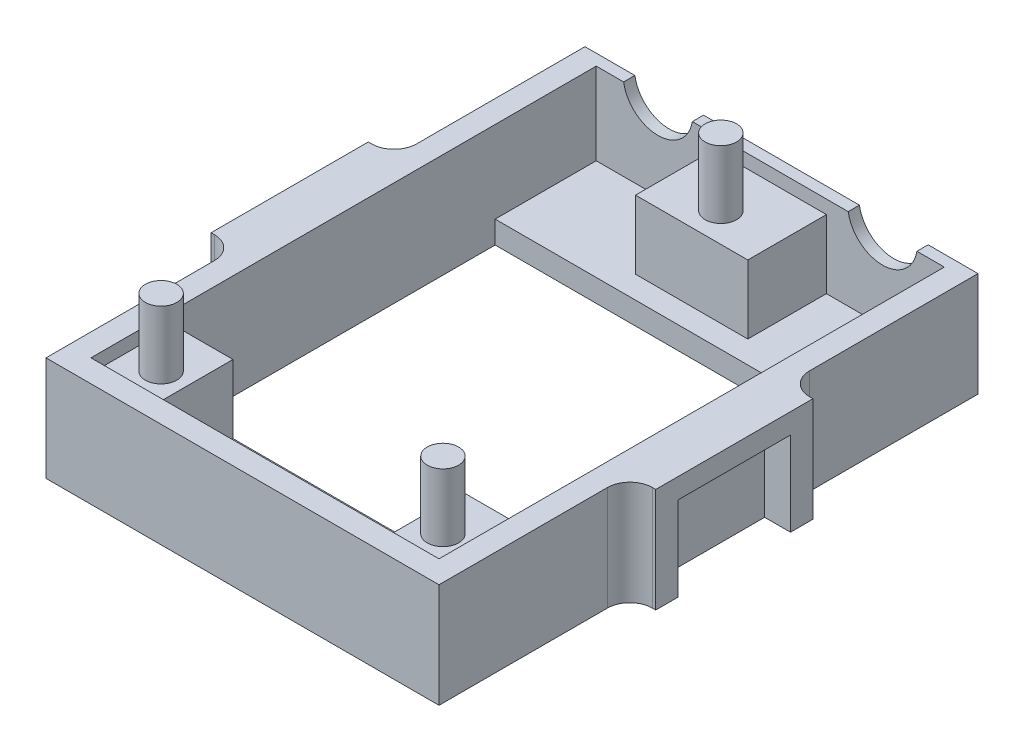
SolidWorks part; units mm, degrees
ref_plane "Front Plane" through (0, 0, 0) normal (0, 0, 1) x (1, 0, 0)
ref_plane "Top Plane" through (0, 0, 0) normal (0, 1, 0) x (1, 0, 0)
ref_plane "Right Plane" through (0, 0, 0) normal (1, 0, 0) x (0, 0, -1)
sketch "Sketch1" plane through (0, 0, 0) normal (0, 1, 0) x (1, 0, 0)
  line L1 (-17.5, 24) -> (17.5, 24)
  line L2 (-17.5, 24) -> (-17.5, -24)
  line L3 (-17.5, -24) -> (17.5, -24)
  line L4 (17.5, 24) -> (17.5, -24)
  line L5 (-44.2539, 0) -> (44.2539, 0) construction
  line L6 (0, -44.7868) -> (0, 44.7868) construction
  dimension "D2" = 35
  dimension "D1" = 48
  dimension "D3" = 24
  dimension "D4" = 17.5
extrude "Boss-Extrude1" add sketch "Sketch1" along normal blind 2
sketch "Sketch2" plane through (0, 2, 0) normal (0, 1, 0) x (1, 0, 0)
  line L1 (-15.5, 23) -> (15.5, 23)
  line L2 (-15.5, 23) -> (-15.5, -21)
  line L3 (-15.5, -21) -> (15.5, -21)
  line L4 (15.5, 23) -> (15.5, -21)
  line L6 (17.5, -24) -> (17.5, 24) construction
  line L7 (-17.5, -24) -> (17.5, -24) construction
  line M5 (-17.5, 24) -> (-17.5, -24)
  line M6 (-17.5, -24) -> (17.5, -24)
  line M7 (17.5, -24) -> (17.5, 24)
  line M8 (17.5, 24) -> (-17.5, 24)
  dimension "D1" = 2
  dimension "D2" = 3
  dimension "D3" = 31
  dimension "D4" = 44
extrude "Boss-Extrude2" add sketch "Sketch2" along normal blind 7.3 contours L1 L4 L3 L2 M8 M5 M6 M7
sketch "Sketch3" plane through (0, 2, 0) normal (0, 1, 0) x (1, 0, 0)
  line L0 (-15.5, 23) -> (15.5, 23) construction
  line L1 (-5, 23) -> (5, 23)
  line L2 (-5, 23) -> (-5, 16)
  line L3 (-5, 16) -> (5, 16)
  line L4 (5, 23) -> (5, 16)
  line L5 (15.5, 23) -> (15.5, -21) construction
  line L7 (-15.5, -21) -> (-10.25, -21)
  line L8 (-15.5, -21) -> (-15.5, -14.6)
  line L9 (-15.5, -14.6) -> (-10.25, -14.6)
  line L10 (-10.25, -21) -> (-10.25, -14.6)
  line L11 (15.5, -21) -> (10.25, -21)
  line L12 (15.5, -21) -> (15.5, -14.6)
  line L13 (15.5, -14.6) -> (10.25, -14.6)
  line L14 (10.25, -21) -> (10.25, -14.6)
  dimension "D1" = 10
  dimension "D2" = 7
  dimension "D3" = 10.5
  dimension "D4" = 5.25
  dimension "D5" = 5.25
  dimension "D6" = 6.4
  dimension "D7" = 6.4
extrude "Boss-Extrude3" add sketch "Sketch3" along normal blind 6.1
sketch "Sketch6" plane through (0, 0, -24) normal (0, 0, -1) x (-1, 0, 0)
  line L1 (-17.5, 9.3) -> (17.5, 9.3) construction
  line L2 (-17.5, 9.3) -> (-17.5, 0) construction
  arc A0 (-6.9406, 9.3) -> (-13.0594, 9.3) centre (-10, 9.8) cw
  arc A1 (13.0594, 9.3) -> (6.9406, 9.3) centre (10, 9.8) cw
  line M3 (17.5, 9.3) -> (-17.5, 9.3)
  dimension "D1" = 7.5
  dimension "D3" = 0.5
  dimension "D4" = 0.5
  dimension "D5" = 3.1
  dimension "D6" = 3.1
  dimension "D2" = 20
sketch "Sketch8" plane through (0, 0, 0) normal (0, 1, 0) x (1, 0, 0)
  line L0 (0, -44.7868) -> (0, 44.7868) construction
  line L2 (17.5, 24) -> (-17.5, 24) construction
  circle A0 centre (-12.55, -18.7) radius 1.4
  circle A1 centre (12.55, -18.7) radius 1.4
  circle A2 centre (0, 18.6) radius 1.4
  dimension "D1" = 2.8
  dimension "D7" = 2.8
  dimension "D8" = 2.8
  dimension "D3" = 25.1
  dimension "D5" = 12.55
  dimension "D6" = 5.4
  dimension "D2" = 37.3
  dimension "D4" = 37.3
sketch "Sketch9" plane through (0, 0, 0) normal (0, 1, 0) x (1, 0, 0)
  line L0 (-35.1135, -20.6) -> (29.9959, -20.6) construction
  line L1 (-15.5, 23) -> (15.5, 23) construction
  line L2 (-35.1135, 21.9) -> (32.5575, 21.9) construction
  point P4 (0, 23)
  dimension "D1" = 43.6
  dimension "D2" = 42.5
extrude "Cut-Extrude5" cut sketch "Sketch6" against normal blind 1 contours A0 M3 | A1 M3
sketch "Sketch10" plane through (0, 2, 0) normal (0, 1, 0) x (1, 0, 0)
  line L0 (-15.5, -14.6) -> (15.5, -14.6)
  line L1 (-15.5, 23) -> (-15.5, -14.6) construction
  line L2 (15.5, 23) -> (15.5, -21) construction
  line L4 (-15.5, 14) -> (15.5, 14)
  line L5 (15.5, 23) -> (15.5, -14.6) construction
  line L6 (-35.1135, 21.9) -> (32.5575, 21.9) construction
  line M5 (15.5, -14.6) -> (15.5, 23)
  line M11 (-15.5, 23) -> (-15.5, -14.6)
  dimension "D1" = 28.6
  dimension "D2" = 7.9
extrude "Cut-Extrude6" cut sketch "Sketch10" against normal through all contours L4 L0 M11 M5
extrude "Boss-Extrude4" add sketch "Sketch8" along normal blind 6 from surface at 8.1 starting at face at (0, 8.1, -19.5)
sketch "Sketch12" plane through (-17.5, 0, 0) normal (-1, 0, 0) x (0, 0, 1)
  line L0 (0, -44.2539) -> (0, 44.2539) construction
  line L1 (-3, 4) -> (3, 4)
  line L2 (-3, 4) -> (-3, 0)
  line L3 (-3, 0) -> (3, 0)
  line L4 (3, 4) -> (3, 0)
  line L6 (55, 0) -> (-55, 0) construction
  dimension "D1" = 6
  dimension "D2" = 4
  dimension "D3" = 3
extrude "Boss-Extrude5" [suppressed] add sketch "Sketch12" along normal blind 3.5
sketch "Sketch13" [suppressed] plane through (0, 4, 0) normal (0, 1, 0) x (1, 0, 0)
  line L0 (-44.2539, 0) -> (44.2539, 0) construction
  line L1 (-17.8, 1.4) -> (-19.8, 1.4)
  line L2 (-17.8, 1.4) -> (-17.8, -1.4)
  line L3 (-17.8, -1.4) -> (-19.8, -1.4)
  line L4 (-19.8, 1.4) -> (-19.8, -1.4)
  line L6 (-21, -3) -> (-21, 3) construction
  dimension "D1" = 2
  dimension "D2" = 2.8
  dimension "D3" = 1.4
  dimension "D4" = 1.2
extrude "Cut-Extrude7" [suppressed] cut sketch "Sketch13" against normal up to surface (4 mm away)
mirror "Mirror1" [suppressed] about plane through (0, 0, 0) normal (1, 0, 0)
sketch "Sketch14" plane through (0, 0, 0) normal (0, 0, 1) x (1, 0, 0)
  line L9 (17.5, 9.3) -> (19.8, 9.3)
  line L10 (19.8, 9.3) -> (19.8, 7.5)
  line L11 (19.8, 7.5) -> (17.5, 7.5)
  line L12 (17.5, 9.3) -> (17.5, 0) construction
  line L13 (17.5, 9.3) -> (17.5, 7.5)
  dimension "D1" = 1.8
  dimension "D2" = 2.3
extrude "Boss-Extrude6" add sketch "Sketch14" along normal mid plane 10
sketch "Sketch15" plane through (17.5, 0, 0) normal (1, 0, 0) x (0, 0, -1)
  line L0 (55, 0) -> (-55, 0) construction
  line L1 (-5, 9.3) -> (-7, 9.3)
  line L2 (-5, 9.3) -> (-5, 0)
  line L3 (-5, 0) -> (-7, 0)
  line L4 (-7, 9.3) -> (-7, 0)
  line L6 (5, 9.3) -> (7, 9.3)
  line L7 (5, 9.3) -> (5, 0)
  line L8 (5, 0) -> (7, 0)
  line L9 (7, 9.3) -> (7, 0)
  dimension "D1" = 2
  dimension "D2" = 2
extrude "Boss-Extrude7" add sketch "Sketch15" along normal blind 2.3
mirror "Mirror3" about plane through (0, 0, 0) normal (1, 0, 0) of "Boss-Extrude6", "Boss-Extrude7"
fillet "Fillet3" radius 2 4 edges at (17.5, 4.65, 7) (17.5, 4.65, -7) (-17.5, 4.65, -7) (-17.5, 4.65, 7)
sketch "Sketch16" plane through (0, 9.3, 0) normal (0, 1, 0) x (1, 0, 0)
  line L1 (-15.5, -21) -> (15.5, -21)
  line L2 (-15.5, -21) -> (-15.5, -22)
  line L3 (-15.5, -22) -> (15.5, -22)
  line L4 (15.5, -21) -> (15.5, -22)
  point P5 (0, 0)
  point P6 (0, 0)
  dimension "D1" = 1
extrude "Cut-Extrude8" cut sketch "Sketch16" against normal up to surface (1.2 mm away) up to face at (-12.55, 8.1, 17.3)
equation "\"fWidth\"=35"
equation "\"D2@Sketch1\"=\"fWidth\""
equation "\"fLength\"= 48"
equation "\"D1@Sketch1\"=\"fLength\""
equation "\"D3@Sketch1\"=\"fLength\"/2"
equation "\"D4@Sketch1\"=\"fWidth\"/2"
equation "\"wThickness\"=2"
equation "\"D1@Sketch2\"=\"wThickness\""
equation "\"D3@Sketch2\"=\"fWidth\"- 2* \"wThickness\""
equation "\"D4@Sketch2\"=\"fLength\"- 2 *\"wThickness\""
equation "\"wHeight\"= 7.3"
equation "\"D1@Boss-Extrude2\"=\"wHeight\""
equation "\"D3@Sketch3\"=(\"fWidth\"- 2 *\"wThickness\" - 10)/2"
equation "\"D1@Boss-Extrude3\"=\"wHeight\""
equation "\"holeDiam\"= 2.8"
equation "\"D8@Sketch8\"=\"holeDiam\""
equation "\"D1@Sketch8\"=\"holeDiam\""
equation "\"D7@Sketch8\"=\"holeDiam\""
